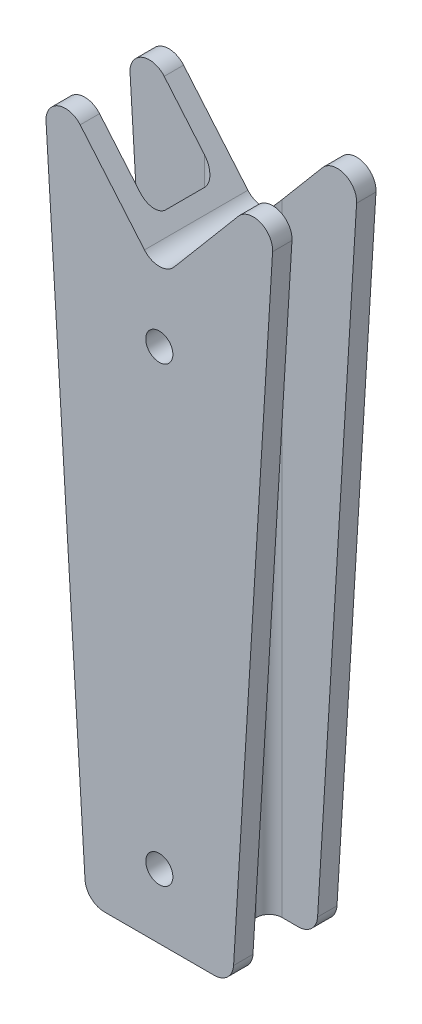
SolidWorks part; units mm, degrees
ref_plane "前视基准面" through (0, 0, 0) normal (0, 0, 1) x (1, 0, 0)
ref_plane "上视基准面" through (0, 0, 0) normal (0, 1, 0) x (1, 0, 0)
ref_plane "右视基准面" through (0, 0, 0) normal (1, 0, 0) x (0, 0, -1)
other "Configuration Table"
sketch "草图1" plane through (0, 0, 0) normal (0, 0, 1) x (1, 0, 0)
  line L0 (-12.2411, 51.269) -> (-2.2925, 39.4827)
  line L1 (-8.4988, -52.334) -> (8.4988, -52.334)
  line L2 (-17.528, 49.1508) -> (-11.4932, -49.5171)
  line L3 (17.528, 49.1508) -> (11.4932, -49.5171)
  line L4 (12.2411, 51.269) -> (2.2925, 39.4827)
  arc A0 (11.4932, -49.5171) -> (8.4988, -52.334) centre (8.4988, -49.334) cw
  arc A1 (-8.4988, -52.334) -> (-11.4932, -49.5171) centre (-8.4988, -49.334) cw
  arc A2 (2.2925, 39.4827) -> (-2.2925, 39.4827) centre (0, 41.4177) cw
  arc A3 (17.528, 49.1508) -> (12.2411, 51.269) centre (14.5336, 49.334) ccw
  arc A4 (-12.2411, 51.269) -> (-17.528, 49.1508) centre (-14.5336, 49.334) ccw
extrude "凸台-拉伸1" add sketch "草图1" along normal blind 3
sketch "草图2" plane through (0, 0, 3) normal (0, 0, 1) x (1, 0, 0)
  line L0 (0, 48.5661) -> (0, -57.1068) construction
  line L1 (-4, -52.334) -> (-4, 41.5056)
  line L2 (-8.4988, -52.334) -> (8.4988, -52.334) construction
  line L3 (-4, 41.5056) -> (-2.2925, 39.4827)
  line L5 (-4, -52.334) -> (4, -52.334)
  line L6 (4, 41.5056) -> (2.2925, 39.4827)
  line L7 (4, -52.334) -> (4, 41.5056)
  line L8 (12.2411, 51.269) -> (2.2925, 39.4827) construction
  arc A0 (-2.2925, 39.4827) -> (2.2925, 39.4827) centre (0, 41.4177) ccw
  point P13 (0, -52.334)
  dimension "D1" = 4
extrude "凸台-拉伸2" add sketch "草图2" along normal blind 10
sketch "草图3" plane through (0, 0, 13) normal (0, 0, 1) x (1, 0, 0)
  line L0 (-12.2411, 51.269) -> (-2.2925, 39.4827)
  line L1 (-8.4988, -52.334) -> (8.4988, -52.334)
  line L2 (-17.528, 49.1508) -> (-11.4932, -49.5171)
  line L3 (17.528, 49.1508) -> (11.4932, -49.5171)
  line L4 (12.2411, 51.269) -> (2.2925, 39.4827)
  line L5 (11.4932, -49.5171) -> (17.528, 49.1508) construction
  line L8 (-4, -52.334) -> (4, -52.334) construction
  line L9 (-17.528, 49.1508) -> (-11.4932, -49.5171) construction
  line L10 (-4, 41.5056) -> (-12.2411, 51.269) construction
  line L11 (12.2411, 51.269) -> (4, 41.5056) construction
  arc A0 (11.4932, -49.5171) -> (8.4988, -52.334) centre (8.4988, -49.334) cw
  arc A1 (-8.4988, -52.334) -> (-11.4932, -49.5171) centre (-8.4988, -49.334) cw
  arc A2 (2.2925, 39.4827) -> (-2.2925, 39.4827) centre (0, 41.4177) cw
  arc A3 (17.528, 49.1508) -> (12.2411, 51.269) centre (14.5336, 49.334) ccw
  arc A4 (-12.2411, 51.269) -> (-17.528, 49.1508) centre (-14.5336, 49.334) ccw
extrude "凸台-拉伸3" add sketch "草图3" along normal blind 3
fillet "圆角1" radius 2 4 edges at (4, -5.4142, 3) (4, -5.4142, 13) (-4, -5.4142, 13) (-4, -5.4142, 3)
sketch "草图4" plane through (0, 0, 16) normal (0, 0, 1) x (1, 0, 0)
  line L2 (-8.4988, -52.334) -> (8.4988, -52.334) construction
  line L3 (0, 38.4177) -> (0, -63.9414) construction
  arc A2 (-2.2925, 39.4827) -> (2.2925, 39.4827) centre (0, 41.4177) ccw construction
  circle A5 centre (0, -42.334) radius 2.1
  circle A6 centre (0, 27.666) radius 2.1
  dimension "D6" = 4.2
  dimension "D7" = 10
  dimension "D8" = 4.2
  dimension "D9" = 70
extrude "切除-拉伸1" cut sketch "草图4" against normal blind 37
